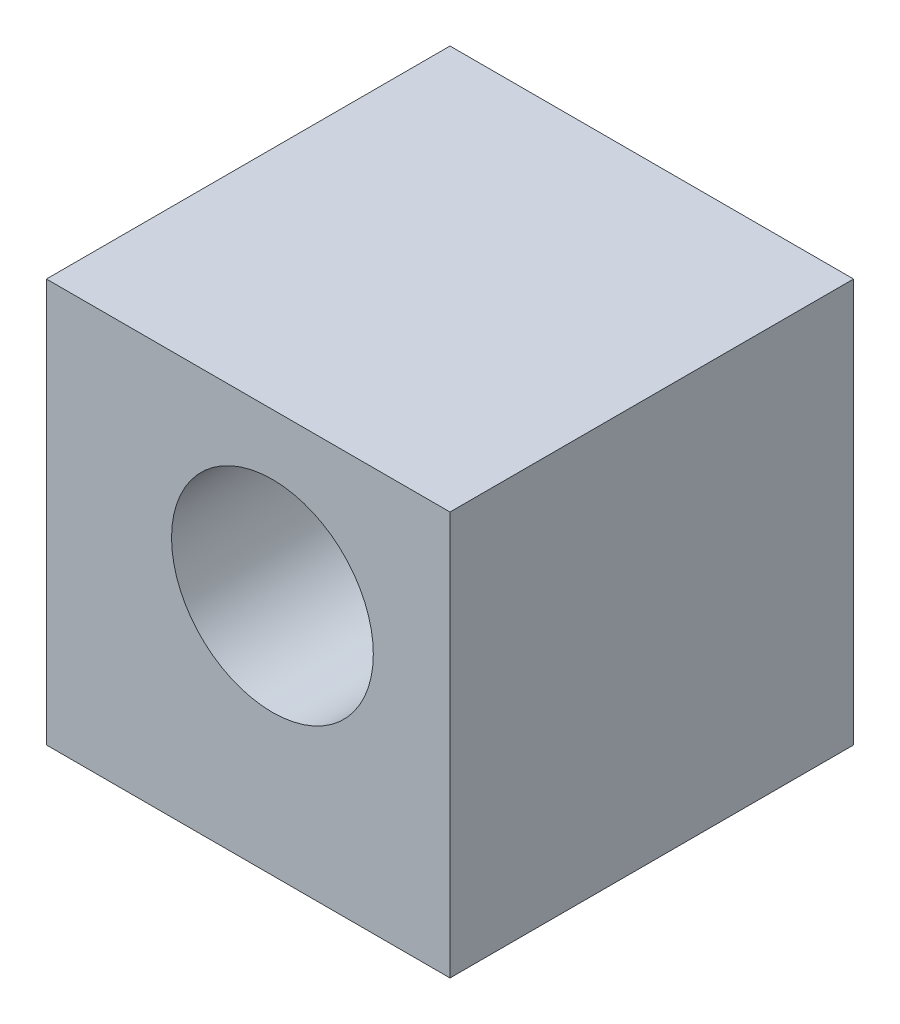
SolidWorks part; units mm, degrees
ref_plane "Piano frontale" through (0, 0, 0) normal (0, 0, 1) x (1, 0, 0)
ref_plane "Piano superiore" through (0, 0, 0) normal (0, 1, 0) x (1, 0, 0)
ref_plane "Piano destro" through (0, 0, 0) normal (1, 0, 0) x (0, 0, -1)
sketch "Schizzo2" plane through (0, 0, 0) normal (0, 0, 1) x (1, 0, 0)
  line L1 (15, -15) -> (-15, -15)
  line L2 (15, -15) -> (15, 15)
  line L3 (15, 15) -> (-15, 15)
  line L4 (-15, -15) -> (-15, 15)
  line L5 (15, -15) -> (-15, 15) construction
  line L6 (15, 15) -> (-15, -15) construction
  circle A0 centre (1.8, 3) radius 7.5
  point P0 (0, 0)
  dimension "D3" = 15
  dimension "D1" = 30
  dimension "D2" = 30
  dimension "D4" = 12
  dimension "D5" = 13.2
extrude "Estrusione-Estrusione1" add sketch "Schizzo2" against normal blind 30
sketch "Schizzo3" plane through (-15, 0, 0) normal (-1, 0, 0) x (0, 0, 1)
  line L0 (-15, -15) -> (-15, 15) construction
  line L1 (-30, -15) -> (0, -15) construction
  line L2 (-30, 15) -> (0, 15) construction
  circle A0 centre (-15, -5) radius 4
  dimension "D1" = 8
  dimension "D2" = 10
extrude "Taglio-Estrusione1" cut sketch "Schizzo3" against normal blind 13
sketch "Schizzo5" plane through (0, -15, 0) normal (0, -1, 0) x (1, 0, 0)
  line L0 (15, -30) -> (15, 0) construction
  line L1 (-15, 0) -> (15, 0) construction
  circle A0 centre (5, -15) radius 4
  dimension "D2" = 8
  dimension "D1" = 10
  dimension "D3" = 15
extrude "Taglio-Estrusione2" cut sketch "Schizzo5" against normal blind 12
